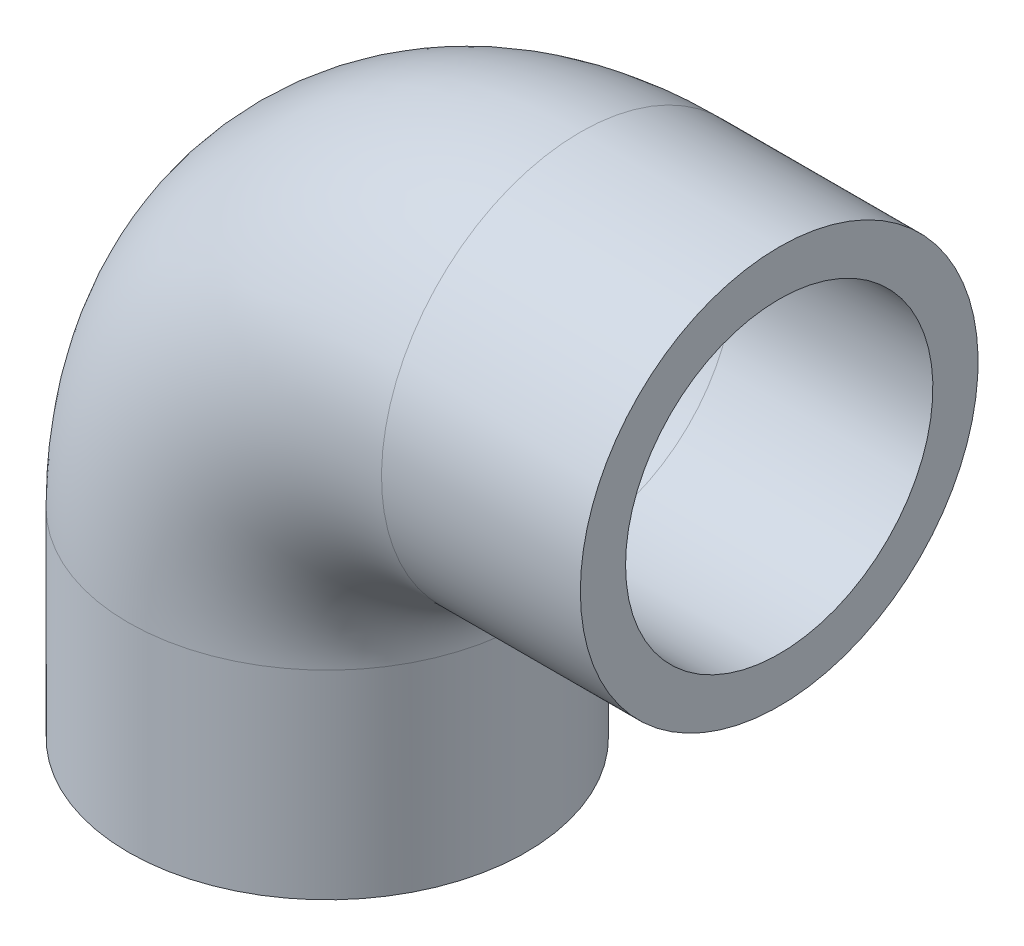
SolidWorks part; units mm, degrees
ref_plane "Front Plane" through (0, 0, 0) normal (0, 0, 1) x (1, 0, 0)
ref_plane "Top Plane" through (0, 0, 0) normal (0, 1, 0) x (1, 0, 0)
ref_plane "Right Plane" through (0, 0, 0) normal (1, 0, 0) x (0, 0, -1)
sketch "Sketch1" plane through (0, 0, 0) normal (0, 0, 1) x (1, 0, 0)
  line L0 (0, 0) -> (0, 13.97)
  line L1 (17.78, 31.75) -> (31.75, 31.75)
  arc A0 (0, 13.97) -> (17.78, 31.75) centre (17.78, 13.97) cw
  point P6 (0, 31.75)
  dimension "D2" = 17.78
  dimension "D1" = 31.75
sweep "Sweep1" add path "Sketch1" circular profile diameter 27.94 parameters "D3"=27.94
ref_plane "Plane1" through (0, 45.72, 0) normal (0, 1, 0) x (1, 0, 0)
shell "Shell1" thickness 3.175
sketch "Sketch28" plane through (0, 0, 0) normal (0, -1, 0) x (1, 0, 0)
  circle A0 centre (0, 0) radius 10.795
  circle A1 centre (0, 0) radius 13.97 construction
  dimension "D1" = 3.175
extrude "Cut-Extrude1" cut sketch "Sketch28" against normal blind 13.208
